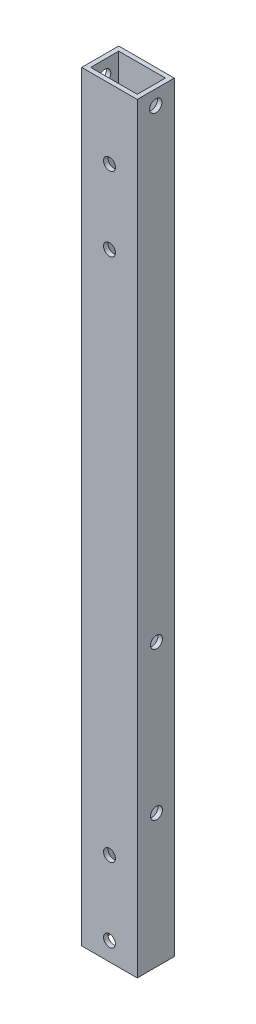
SolidWorks part; units mm, degrees
ref_plane "正面" through (0, 0, 0) normal (0, 0, 1) x (1, 0, 0)
ref_plane "平面" through (0, 0, 0) normal (0, 1, 0) x (1, 0, 0)
ref_plane "右側面" through (0, 0, 0) normal (1, 0, 0) x (0, 0, -1)
sketch "ｽｹｯﾁ1" plane through (0, 0, 0) normal (0, 1, 0) x (1, 0, 0)
  line L0 (-6.3, 3.8) -> (6.3, 3.8)
  line L1 (-7.5, 5) -> (7.5, 5)
  line L2 (-7.5, 5) -> (-7.5, -5)
  line L3 (-7.5, -5) -> (7.5, -5)
  line L4 (7.5, 5) -> (7.5, -5)
  line L5 (-7.5, 5) -> (7.5, -5) construction
  line L6 (-7.5, -5) -> (7.5, 5) construction
  line L7 (6.3, 3.8) -> (6.3, -3.8)
  line L8 (-6.3, -3.8) -> (6.3, -3.8)
  line L9 (-6.3, 3.8) -> (-6.3, -3.8)
  point P0 (0, 0)
  dimension "D1" = 15
  dimension "D2" = 10
  dimension "D3" = 1.2
extrude "ﾎﾞｽ - 押し出し1" add sketch "ｽｹｯﾁ1" along normal mid plane 220
sketch "ｽｹｯﾁ2" plane through (0, 0, -5) normal (0, 0, -1) x (-1, 0, 0)
  line L0 (0, -110) -> (0, -85) construction
  line L1 (-7.5, -110) -> (7.5, -110) construction
  circle A0 centre (0, -85) radius 1.6
  circle A1 centre (0, -105) radius 1.6
  dimension "D2" = 3.2
  dimension "D3" = 3.2
  dimension "D1" = 25
  dimension "D4" = 20
extrude "ｶｯﾄ - 押し出し1" cut sketch "ｽｹｯﾁ2" against normal blind 100
sketch "ｽｹｯﾁ3" plane through (-7.5, 0, 0) normal (-1, 0, 0) x (0, 0, 1)
  line L0 (0, -110) -> (0, 0) construction
  line L1 (-5, -110) -> (5, -110) construction
  circle A0 centre (-0.2, -74) radius 1.6
  circle A1 centre (-0.2, -34) radius 1.6
  dimension "D1" = 3.2
  dimension "D2" = 3.2
extrude "ｶｯﾄ - 押し出し2" cut sketch "ｽｹｯﾁ3" against normal blind 15
sketch "ｽｹｯﾁ5" plane through (0, 110, 0) normal (0, 1, 0) x (1, 0, 0)
  line L4 (7.5, -5) -> (7.5, 5)
  line L5 (7.5, 5) -> (-7.5, 5)
  line L6 (-7.5, 5) -> (-7.5, -5)
  line L7 (-7.5, -5) -> (7.5, -5)
  line L8 (7.5, -5) -> (7.5, 5)
  line L9 (7.5, 5) -> (-7.5, 5)
  line L10 (-7.5, 5) -> (-7.5, -5)
  line L11 (-7.5, -5) -> (7.5, -5)
  dimension "D1" = 0
extrude "ｶｯﾄ - 押し出し4" cut sketch "ｽｹｯﾁ5" against normal blind 14.5
sketch "ｽｹｯﾁ6" plane through (0, 0, -5) normal (0, 0, -1) x (-1, 0, 0)
  line L0 (0, 95.5) -> (0, 90.5) construction
  line L1 (-7.5, 95.5) -> (7.5, 95.5) construction
  line L2 (0, 90.5) -> (0, 76.66) construction
  line L3 (0, 76.66) -> (0, 56.66) construction
  circle A0 centre (0, 90.5) radius 1.6
  circle A1 centre (0, 76.66) radius 1.6
  circle A2 centre (0, 56.66) radius 1.6
  dimension "D2" = 3.2
  dimension "D4" = 3.2
  dimension "D6" = 3.2
  dimension "D1" = 5
  dimension "D3" = 13.84
  dimension "D5" = 20
extrude "ｶｯﾄ - 押し出し5" cut sketch "ｽｹｯﾁ6" against normal blind 15 contours A2 | A1
sketch "ｽｹｯﾁ7" plane through (-7.5, 0, 0) normal (-1, 0, 0) x (0, 0, 1)
  arc A0 (0, 93.15) -> (0, 89.85) centre (0, 91.5) ccw construction
  arc A1 (0, 89.85) -> (0, 93.15) centre (0, 91.5) ccw construction
  arc A2 (0, 93.15) -> (0, 89.85) centre (0, 91.5) ccw
  arc A3 (0, 89.85) -> (0, 93.15) centre (0, 91.5) ccw
extrude "ｶｯﾄ - 押し出し6" cut sketch "ｽｹｯﾁ7" against normal blind 15
